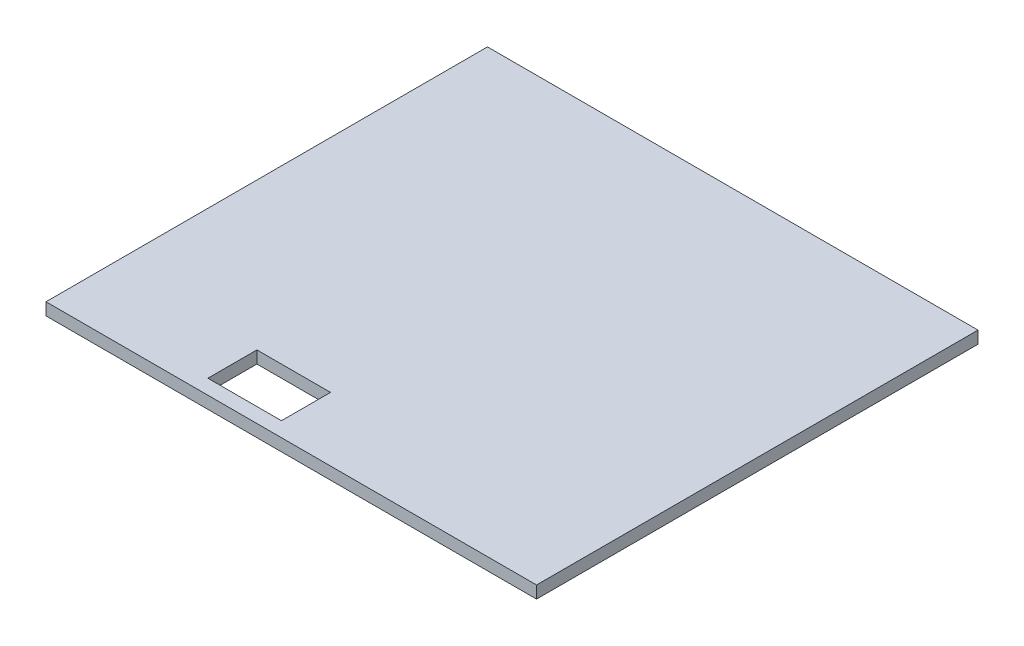
SolidWorks part; units mm, degrees
ref_plane "Front Plane" through (0, 0, 0) normal (0, 0, 1) x (1, 0, 0)
ref_plane "Top Plane" through (0, 0, 0) normal (0, 1, 0) x (1, 0, 0)
ref_plane "Right Plane" through (0, 0, 0) normal (1, 0, 0) x (0, 0, -1)
sketch "Sketch1" plane through (0, 0, 0) normal (0, 1, 0) x (1, 0, 0)
  line L1 (50, -45) -> (-50, -45)
  line L2 (50, -45) -> (50, 45)
  line L3 (50, 45) -> (-50, 45)
  line L4 (-50, -45) -> (-50, 45)
  line L5 (50, -45) -> (-50, 45) construction
  line L6 (50, 45) -> (-50, -45) construction
  line L7 (-20, -32) -> (-5, -32)
  line L8 (-20, -32) -> (-20, -42)
  line L9 (-20, -42) -> (-5, -42)
  line L10 (-5, -32) -> (-5, -42)
  line L11 (-20, -32) -> (-5, -42) construction
  line L12 (-20, -42) -> (-5, -32) construction
  point P0 (0, 0)
  point P6 (-12.5, -37)
  dimension "D1" = 100
  dimension "D2" = 90
  dimension "D3" = 10
  dimension "D4" = 15
  dimension "D5" = 8
  dimension "D6" = 37.5
extrude "Boss-Extrude1" add sketch "Sketch1" along normal blind 2.5
